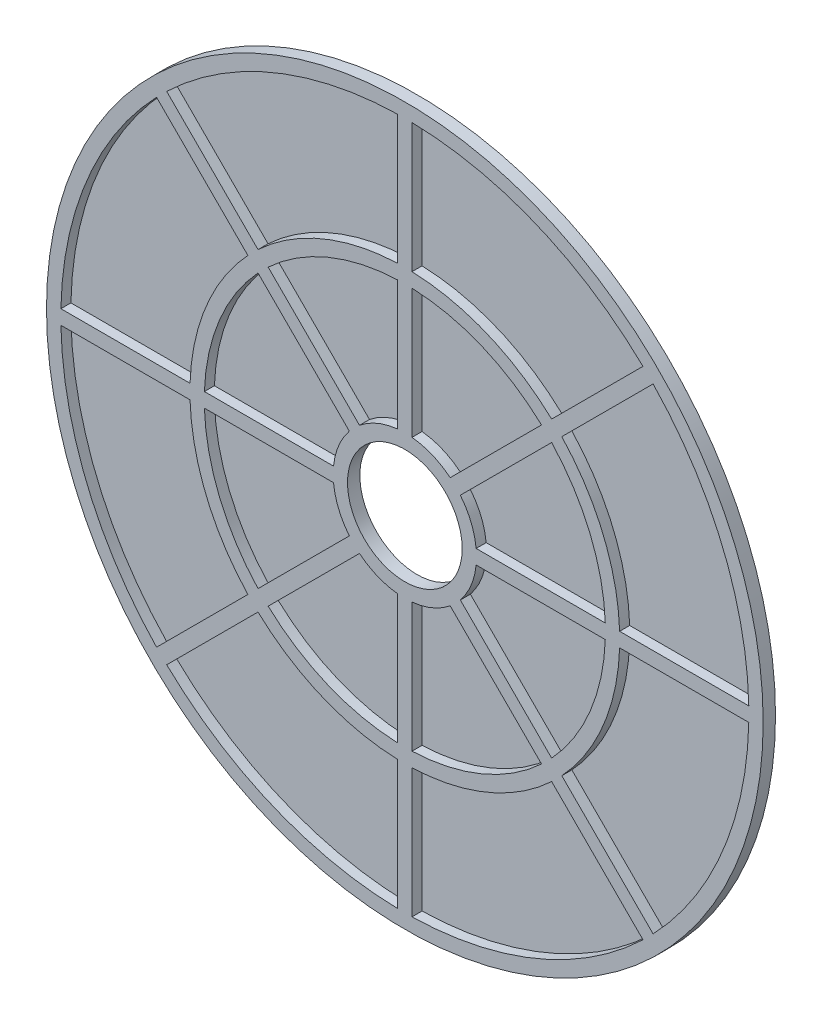
SolidWorks part; units mm, degrees
material "Ti-6Al-4VSolution treated and aged (SS)"
ref_plane "Front Plane" through (0, 0, 0) normal (0, 0, 1) x (1, 0, 0)
ref_plane "Top Plane" through (0, 0, 0) normal (0, 1, 0) x (1, 0, 0)
ref_plane "Right Plane" through (0, 0, 0) normal (1, 0, 0) x (0, 0, -1)
sketch "Sketch1" plane through (0, 0, 0) normal (0, 0, 1) x (1, 0, 0)
  circle A0 centre (0, 0) radius 250
  circle A1 centre (0, 0) radius 40
  dimension "D1" = 500
  dimension "D2" = 80
extrude "Boss-Extrude1" add sketch "Sketch1" along normal blind 1.6
sketch "Sketch3" plane through (0, 0, 1.6) normal (0, 0, 1) x (1, 0, 0)
  circle A0 centre (0, 0) radius 40 construction
  circle A1 centre (0, 0) radius 250 construction
  circle A2 centre (0, 0) radius 40
  circle A3 centre (0, 0) radius 250
  circle A4 centre (0, 0) radius 240
  circle A5 centre (0, 0) radius 50
  circle M2 centre (0, 0) radius 250
  circle M3 centre (0, 0) radius 40
  dimension "D1" = 10
  dimension "D2" = 10
extrude "Boss-Extrude2" add sketch "Sketch3" along normal blind 7 contours A5 M3 | M3 | A4 M2 | A2
sketch "Sketch4" plane through (0, 0, 8.6) normal (0, 0, 1) x (1, 0, 0)
  line L0 (50, 0) -> (240, 0)
  circle A0 centre (0, 0) radius 50 construction
  circle A1 centre (0, 0) radius 240 construction
rib "Rib2" sketch "Sketch4" sketch "Sketch4" thickness 10 extrusion direction normal to sketch draft on no parameters "D1"=10
pattern_circular "CirPattern1" count 8 over 360 about axis through (0, 0, 0) along (0, 0, 1) of "Rib2"
sketch "Sketch5" plane through (0, 0, 8.6) normal (0, 0, 1) x (1, 0, 0)
  line L0 (239.9479, 5) -> (49.7494, 5) construction
  circle A0 centre (0, 0) radius 144.9349
  point P3 (144.8486, 5)
extrude "Extrude-Thin1" add sketch "Sketch5" against normal through all thin
